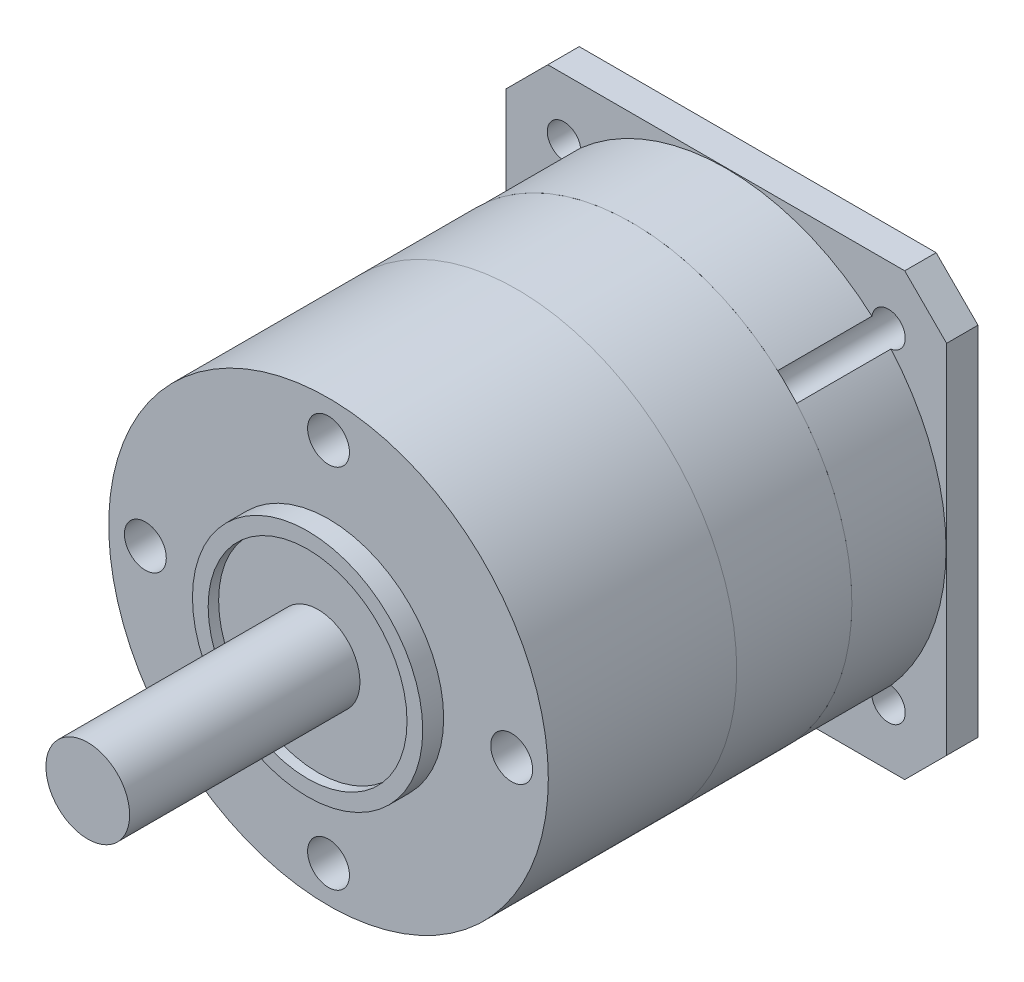
SolidWorks part; units mm, degrees
material "AISI 1020"
ref_plane "Front Plane" through (0, 0, 0) normal (0, 0, 1) x (1, 0, 0)
ref_plane "Top Plane" through (0, 0, 0) normal (0, 1, 0) x (1, 0, 0)
ref_plane "Right Plane" through (0, 0, 0) normal (1, 0, 0) x (0, 0, -1)
sketch "Sketch1" plane through (0, 0, 0) normal (0, 0, 1) x (1, 0, 0)
  line L1 (21.05, -21.05) -> (-21.05, -21.05)
  line L2 (21.05, -21.05) -> (21.05, 21.05)
  line L3 (21.05, 21.05) -> (-21.05, 21.05)
  line L4 (-21.05, -21.05) -> (-21.05, 21.05)
  line L5 (21.05, -21.05) -> (-21.05, 21.05) construction
  line L6 (21.05, 21.05) -> (-21.05, -21.05) construction
  point P0 (0, 0)
  dimension "D1" = 42.1
extrude "Boss-Extrude2" add sketch "Sketch1" along normal blind 3
sketch "Sketch3" plane through (0, 0, 3) normal (0, 0, 1) x (1, 0, 0)
  circle A0 centre (0, 0) radius 21
  dimension "D1" = 42
extrude "Boss-Extrude3" add sketch "Sketch3" along normal offset from surface (9 mm away) 12 up to face at (0, 0, 0)
sketch "Sketch4" plane through (0, 0, 12) normal (0, 0, 1) x (1, 0, 0)
  circle A1 centre (0, 0) radius 21
  circle A2 centre (0, 0) radius 21
  dimension "D1" = 0
extrude "Boss-Extrude4" add sketch "Sketch4" along normal offset from surface (11 mm away) 23 separate body up to face at (0, 0, 0)
sketch "Sketch5" plane through (0, 0, 23) normal (0, 0, 1) x (1, 0, 0)
  circle A1 centre (0, 0) radius 21
  circle A2 centre (0, 0) radius 21
  dimension "D1" = 0
extrude "Boss-Extrude5" add sketch "Sketch5" along normal offset from surface (18 mm away) 41 separate body up to face at (0, 0, 0)
sketch "Sketch6" plane through (0, 0, 41) normal (0, 0, 1) x (1, 0, 0)
  circle A0 centre (0, 0) radius 11
  circle A1 centre (0, 0) radius 9.5 construction
  dimension "D2" = 22
extrude "Boss-Extrude6" add sketch "Sketch6" along normal blind 2
sketch "Sketch9" plane through (0, 0, 43) normal (0, 0, 1) x (1, 0, 0)
  circle A3 centre (0, 0) radius 9.5
  dimension "D1" = 19
extrude "Cut-Extrude2" cut sketch "Sketch9" against normal blind 1
sketch "Sketch7" plane through (0, 0, 41) normal (0, 0, 1) x (1, 0, 0)
  circle A0 centre (0, 0) radius 4
  dimension "D1" = 8
extrude "Boss-Extrude7" add sketch "Sketch7" along normal blind 23 separate body
sketch "Sketch10" plane through (0, 0, 0) normal (0, 0, -1) x (-1, 0, 0)
  line L1 (15.5, -15.5) -> (-15.5, -15.5) construction
  line L2 (15.5, -15.5) -> (15.5, 15.5) construction
  line L3 (15.5, 15.5) -> (-15.5, 15.5) construction
  line L4 (-15.5, -15.5) -> (-15.5, 15.5) construction
  line L5 (15.5, -15.5) -> (-15.5, 15.5) construction
  line L6 (15.5, 15.5) -> (-15.5, -15.5) construction
  circle A0 centre (-15.5, 15.5) radius 1.6
  circle A1 centre (15.5, 15.5) radius 1.6
  circle A2 centre (15.5, -15.5) radius 1.6
  circle A3 centre (-15.5, -15.5) radius 1.6
  point P0 (0, 0)
  dimension "D2" = 3.2
  dimension "D1" = 31
extrude "Cut-Extrude3" cut sketch "Sketch10" against normal up to next
sketch "Sketch12" plane through (0, 0, 41) normal (0, 0, 1) x (1, 0, 0)
  circle A4 centre (0, 0) radius 17.5 construction
  circle A5 centre (0, 17.5) radius 2
  circle A6 centre (17.5, 0) radius 2
  circle A7 centre (0, -17.5) radius 2
  circle A8 centre (-17.5, 0) radius 2
  point P14 (0, 0)
  dimension "D1" = 35
  dimension "D3" = 4
  dimension "D2" = 4
extrude "Cut-Extrude5" cut sketch "Sketch12" against normal blind 10
chamfer "Chamfer1" distance 4 angle 45 4 edges at (21.05, -21.05, 1.5) (-21.05, -21.05, 1.5) (21.05, 21.05, 1.5) (-21.05, 21.05, 1.5)
sketch "Sketch15" plane through (0, 0, 0) normal (0, 0, -1) x (-1, 0, 0)
  circle A0 centre (0, 0) radius 11
  dimension "D1" = 22
extrude "Cut-Extrude8" cut sketch "Sketch15" against normal blind 1.5
